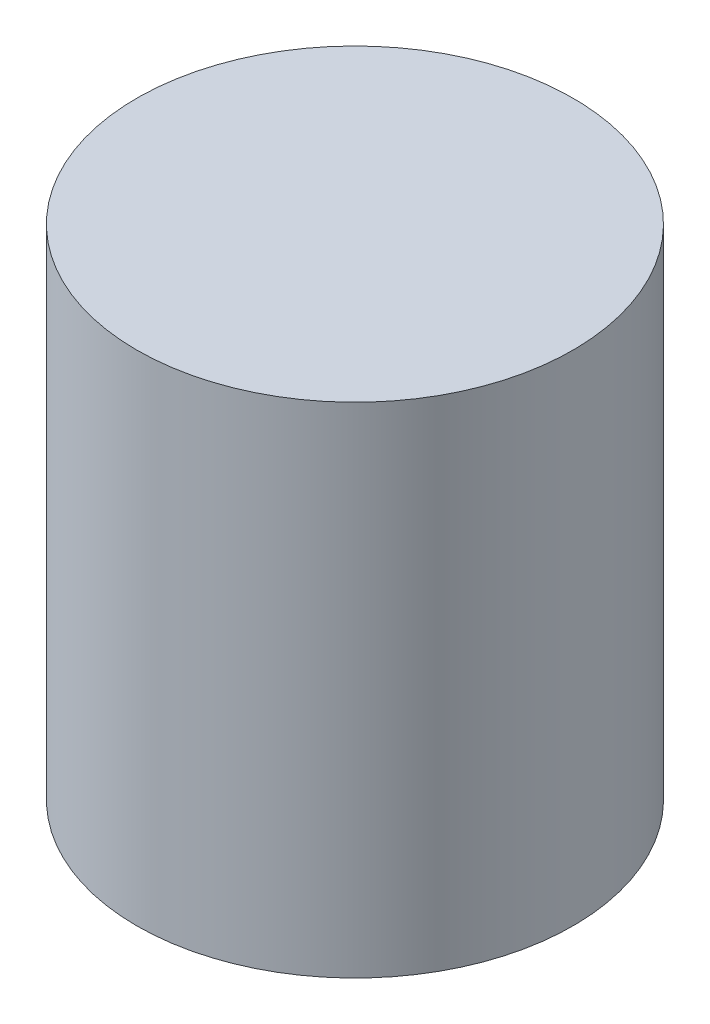
SolidWorks part; units mm, degrees
ref_plane "前视基准面" through (0, 0, 0) normal (0, 0, 1) x (1, 0, 0)
ref_plane "上视基准面" through (0, 0, 0) normal (0, 1, 0) x (1, 0, 0)
ref_plane "右视基准面" through (0, 0, 0) normal (1, 0, 0) x (0, 0, -1)
sketch "草图1" plane through (0, 0, 0) normal (0, 1, 0) x (1, 0, 0)
  circle A0 centre (0, 0) radius 17.5
  dimension "D1" = 35
extrude "凸台-拉伸1" add sketch "草图1" along normal blind 40
sketch "草图2" plane through (0, 0, 0) normal (0, -1, 0) x (1, 0, 0)
  circle A0 centre (0, 0) radius 12
extrude "切除-拉伸1" cut sketch "草图2" against normal blind 20
